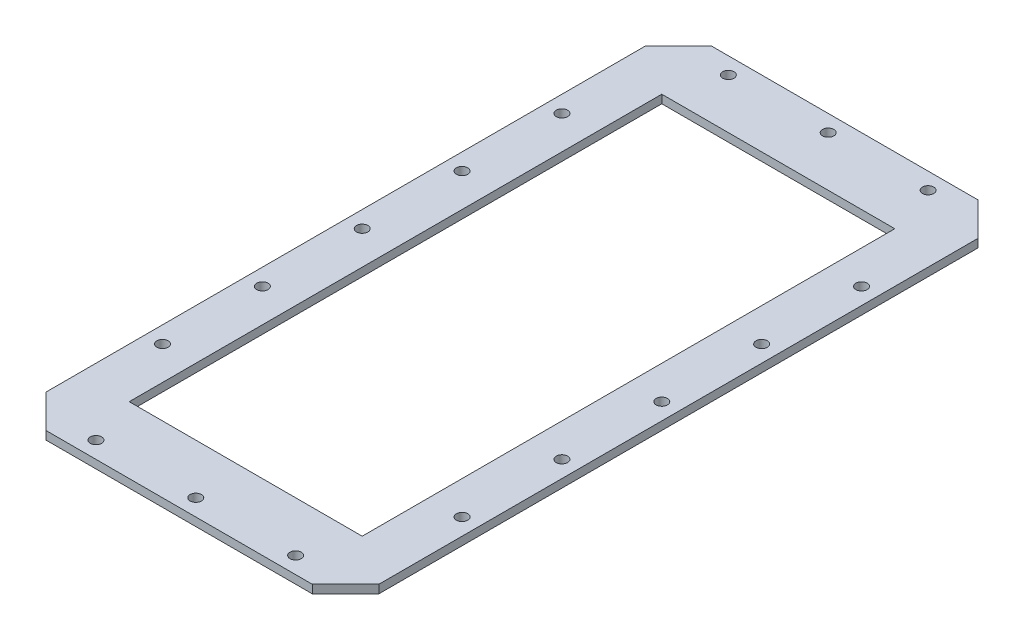
SolidWorks part; units mm, degrees
ref_plane "Front Plane" through (0, 0, 0) normal (0, 0, 1) x (1, 0, 0)
ref_plane "Top Plane" through (0, 0, 0) normal (0, 1, 0) x (1, 0, 0)
ref_plane "Right Plane" through (0, 0, 0) normal (1, 0, 0) x (0, 0, -1)
sketch "Sketch2" plane through (0, 0, 0) normal (0, 1, 0) x (1, 0, 0)
  line L0 (0, 12.7) -> (0, 241.3)
  line L1 (12.7, 254) -> (114.3, 254)
  line L2 (127, 241.3) -> (127, 12.7)
  line L3 (114.3, 0) -> (12.7, 0)
  line L4 (0, 241.3) -> (12.7, 254)
  line L5 (114.3, 254) -> (127, 241.3)
  line L6 (127, 12.7) -> (114.3, 0)
  line L7 (12.7, 0) -> (0, 12.7)
  line L8 (63.5, 254) -> (63.5, -20.3774) construction
  line L10 (0, 127) -> (136.1553, 127) construction
  line L11 (19.05, 228.6) -> (107.95, 228.6)
  line L12 (19.05, 228.6) -> (19.05, 25.4)
  line L13 (19.05, 25.4) -> (107.95, 25.4)
  line L14 (107.95, 228.6) -> (107.95, 25.4)
  line L17 (19.05, 228.6) -> (107.95, 25.4) construction
  line L18 (19.05, 25.4) -> (107.95, 228.6) construction
  circle A1 centre (6.35, 165.1) radius 2.159
  circle A13 centre (25.4, 247.65) radius 2.159
  circle A42 centre (6.35, 203.2) radius 2.159
  circle A43 centre (63.5, 247.65) radius 2.159
  circle A46 centre (6.35, 127) radius 2.159
  circle A56 centre (120.65, 127) radius 2.159
  circle A57 centre (120.65, 165.1) radius 2.159
  circle A58 centre (120.65, 203.2) radius 2.159
  circle A59 centre (101.6, 247.65) radius 2.159
  circle A60 centre (101.6, 6.35) radius 2.159
  circle A61 centre (63.5, 6.35) radius 2.159
  circle A62 centre (25.4, 6.35) radius 2.159
  circle A63 centre (120.65, 50.8) radius 2.159
  circle A64 centre (6.35, 50.8) radius 2.159
  circle A65 centre (120.65, 88.9) radius 2.159
  circle A66 centre (6.35, 88.9) radius 2.159
  point P0 (63.5, 127)
  point P37 (127, 127)
  point P42 (63.5, 0)
  dimension "D8" = 19.05
  dimension "D9" = 12.7
  dimension "D14" = 101.6
  dimension "D16" = 12.7
  dimension "D17" = 254
  dimension "D22" = 228.6
  dimension "D24" = 38.1
  dimension "D30" = 38.1
  dimension "D32" = 4.318
  dimension "D33" = 4.318
  dimension "D36" = 101.6
  dimension "D37" = 228.6
  dimension "D44" = 4.318
  dimension "D45" = 6.35
  dimension "D49" = 4.318
  dimension "D50" = 4.318
  dimension "D51" = 6.35
  dimension "D7" = 127
  dimension "D15" = 12.7
  dimension "D67" = 38.1
extrude "Boss-Extrude1" add sketch "Sketch2" along normal blind 3.175
